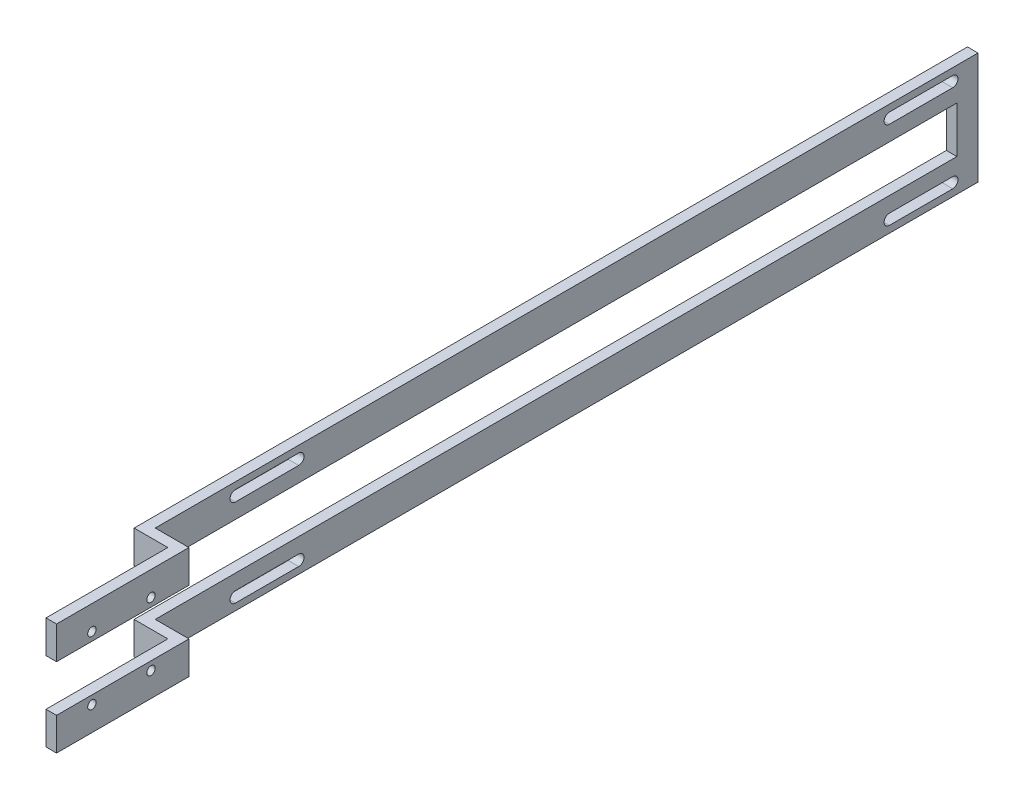
SolidWorks part; units mm, degrees
ref_plane "前视基准面" through (0, 0, 0) normal (0, 0, 1) x (1, 0, 0)
ref_plane "上视基准面" through (0, 0, 0) normal (0, 1, 0) x (1, 0, 0)
ref_plane "右视基准面" through (0, 0, 0) normal (1, 0, 0) x (0, 0, -1)
sketch "草图1" plane through (0, 0, 0) normal (0, 1, 0) x (1, 0, 0)
  line L0 (0, 0) -> (0, 70)
  line L1 (0, 70) -> (-16, 70)
  line L2 (-16, 70) -> (-16, 465)
  line L3 (-16, 465) -> (-11, 465)
  line L4 (-11, 465) -> (-11, 75)
  line L5 (-11, 75) -> (5, 75)
  line L6 (5, 75) -> (5, 0)
  line L7 (0, 0) -> (-42.2396, 0)
  line L8 (-42.2396, 0) -> (-42.2396, -16.0477)
  line L9 (-42.2396, -16.0477) -> (5, -16.0477)
  line L10 (5, -16.0477) -> (5, 0)
  dimension "D1" = 75
  dimension "D2" = 70
  dimension "D3" = 16
  dimension "D4" = 16
  dimension "D5" = 5
  dimension "D6" = 390
extrude "凸台-拉伸1" add sketch "草图1" along normal blind 53
sketch "草图2" plane through (5, 0, 0) normal (1, 0, 0) x (0, 0, -1)
  line L0 (-16.0477, 53) -> (75, 53) construction
  line L1 (0, 37.5) -> (75, 37.5)
  line L2 (0, 37.5) -> (0, 15.5)
  line L3 (0, 15.5) -> (75, 15.5)
  line L4 (75, 37.5) -> (75, 15.5)
  line L7 (55.2866, 37.5) -> (55.2866, 53) construction
  line L8 (55.2866, 15.5) -> (55.2866, 0) construction
  line L9 (-16.0477, 0) -> (75, 0) construction
  line L10 (0, 0) -> (0, 53) construction
  dimension "D1" = 22
extrude "切除-拉伸2" cut sketch "草图2" against normal up to next
sketch "草图3" plane through (-11, 0, 0) normal (1, 0, 0) x (0, 0, -1)
  line L0 (75, 37.5) -> (455, 37.5)
  line L1 (455, 37.5) -> (455, 15.5)
  line L2 (455, 15.5) -> (75, 15.5)
  line L3 (75, 15.5) -> (75, 0) construction
  line L4 (75, 37.5) -> (75, 15.5) construction
  line L5 (75, 15.5) -> (75, 37.5)
  line L6 (455, 37.5) -> (465, 37.5) construction
  line L7 (465, 53) -> (465, 0) construction
  line L8 (455, 37.5) -> (455, 53) construction
  line L9 (75, 53) -> (465, 53) construction
  line L10 (455, 15.5) -> (455, 0) construction
  line L11 (75, 0) -> (465, 0) construction
  dimension "D1" = 10
  dimension "D2" = 22
sketch "草图4" plane through (0, 0, 0) normal (-1, 0, 0) x (0, 0, 1)
  line L0 (-70, 15.5) -> (-70, 37.5) construction
  line L1 (0, 37.5) -> (-70, 37.5) construction
  line L2 (-70, 53) -> (-70, 37.5) construction
  line L3 (-70, 26.5) -> (-57, 26.5) construction
  line L4 (-57, 26.5) -> (-57, 41.5) construction
  line L5 (-57, 26.5) -> (-57, 11.5) construction
  line L6 (-57, 11.5) -> (-29, 11.5) construction
  line L7 (-57, 41.5) -> (-29, 41.5) construction
  circle A0 centre (-57, 11.5) radius 2
  circle A1 centre (-57, 41.5) radius 2
  circle A2 centre (-29, 11.5) radius 2
  circle A3 centre (-29, 41.5) radius 2
  dimension "D3" = 4
  dimension "D4" = 4
  dimension "D7" = 4
  dimension "D8" = 4
  dimension "D1" = 15
  dimension "D2" = 15
  dimension "D5" = 28
  dimension "D6" = 28
  dimension "D9" = 13
extrude "切除-拉伸5" cut sketch "草图4" against normal up to next
extrude "切除-拉伸6" cut sketch "草图3" against normal up to next
sketch "草图5" plane through (-16, 0, 0) normal (-1, 0, 0) x (0, 0, 1)
  line L0 (-70, 15.5) -> (-70, 37.5) construction
  line L1 (-70, 26.5) -> (-143, 26.5) construction
  line L2 (-143, 26.5) -> (-143, 5.75) construction
  line L3 (-143, 26.5) -> (-143, 47.25) construction
  line L4 (-143, 5.75) -> (-113, 5.75) construction
  line L5 (-143, 8.3) -> (-113, 8.3)
  line L6 (-143, 3.2) -> (-113, 3.2)
  line L7 (-143, 47.25) -> (-113, 47.25) construction
  line L8 (-143, 49.8) -> (-113, 49.8)
  line L9 (-143, 44.7) -> (-113, 44.7)
  line L10 (-143, 5.75) -> (-423, 5.75) construction
  line L11 (-423, 5.75) -> (-423, 47.25) construction
  line L12 (-423, 5.75) -> (-453, 5.75) construction
  line L13 (-423, 3.25) -> (-453, 3.25)
  line L14 (-423, 8.25) -> (-453, 8.25)
  line L15 (-423, 47.25) -> (-453, 47.25) construction
  line L16 (-423, 44.75) -> (-453, 44.75)
  line L17 (-423, 49.75) -> (-453, 49.75)
  arc A0 (-143, 8.3) -> (-143, 3.2) centre (-143, 5.75) ccw
  arc A1 (-113, 3.2) -> (-113, 8.3) centre (-113, 5.75) ccw
  arc A2 (-143, 49.8) -> (-143, 44.7) centre (-143, 47.25) ccw
  arc A3 (-113, 44.7) -> (-113, 49.8) centre (-113, 47.25) ccw
  arc A4 (-423, 3.25) -> (-423, 8.25) centre (-423, 5.75) ccw
  arc A5 (-453, 8.25) -> (-453, 3.25) centre (-453, 5.75) ccw
  arc A6 (-423, 44.75) -> (-423, 49.75) centre (-423, 47.25) ccw
  arc A7 (-453, 49.75) -> (-453, 44.75) centre (-453, 47.25) ccw
  point P8 (-128, 5.75)
  point P14 (-128, 47.25)
  point P22 (-438, 5.75)
  point P29 (-438, 47.25)
  dimension "D3" = 2.55
  dimension "D4" = 2.55
  dimension "D12" = 2.5
  dimension "D13" = 2.5
  dimension "D1" = 73
  dimension "D2" = 30
  dimension "D5" = 20.75
  dimension "D6" = 20.75
  dimension "D7" = 30
  dimension "D8" = 41.5
  dimension "D9" = 30
  dimension "D10" = 30
  dimension "D11" = 280
extrude "切除-拉伸7" cut sketch "草图5" against normal up to next
sketch "草图6" plane through (0, 53, 0) normal (0, 1, 0) x (1, 0, 0)
  line L1 (-62.7876, 12.237) -> (31.0814, 12.237)
  line L2 (-62.7876, 12.237) -> (-62.7876, -28.7079)
  line L3 (-62.7876, -28.7079) -> (31.0814, -28.7079)
  line L4 (31.0814, 12.237) -> (31.0814, -28.7079)
extrude "切除-拉伸8" cut sketch "草图6" against normal through all
